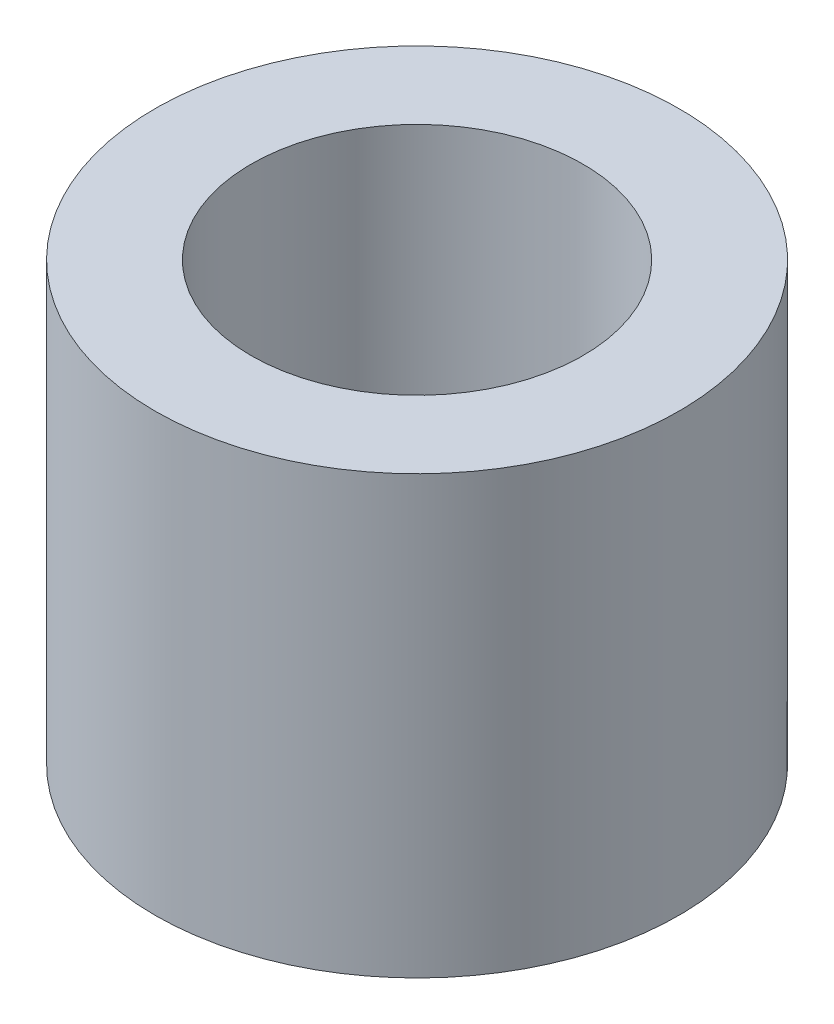
SolidWorks part; units mm, degrees
ref_plane "Front Plane" through (0, 0, 0) normal (0, 0, 1) x (1, 0, 0)
ref_plane "Top Plane" through (0, 0, 0) normal (0, 1, 0) x (1, 0, 0)
ref_plane "Right Plane" through (0, 0, 0) normal (1, 0, 0) x (0, 0, -1)
sketch "Sketch1" plane through (0, 0, 0) normal (0, 1, 0) x (1, 0, 0)
  circle A0 centre (0, 0) radius 1.9
  circle A1 centre (0, 0) radius 3
  dimension "D1" = 3.8
  dimension "D2" = 6
extrude "Boss-Extrude1" add sketch "Sketch1" along normal blind 5
